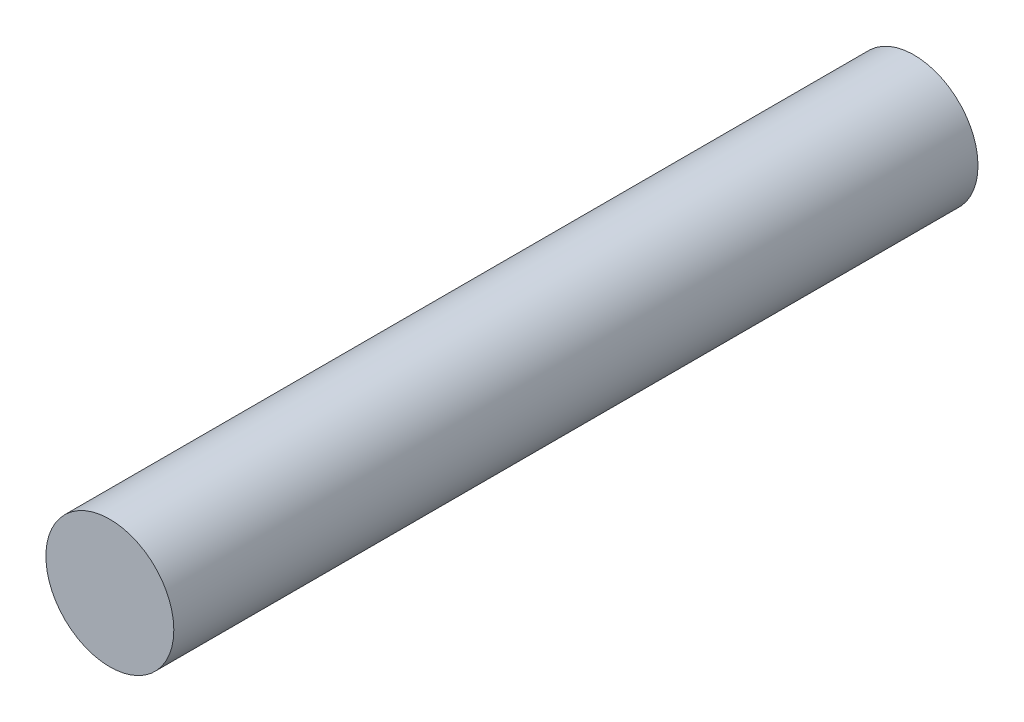
SolidWorks part; units mm, degrees
ref_plane "Front Plane" through (0, 0, 0) normal (0, 0, 1) x (1, 0, 0)
ref_plane "Top Plane" through (0, 0, 0) normal (0, 1, 0) x (1, 0, 0)
ref_plane "Right Plane" through (0, 0, 0) normal (1, 0, 0) x (0, 0, -1)
sketch "Sketch1" plane through (0, 0, 0) normal (0, 0, 1) x (1, 0, 0)
  circle A0 centre (0, 0) radius 1.75
  dimension "D1" = 3.5
extrude "Boss-Extrude1" add sketch "Sketch1" along normal blind 22
